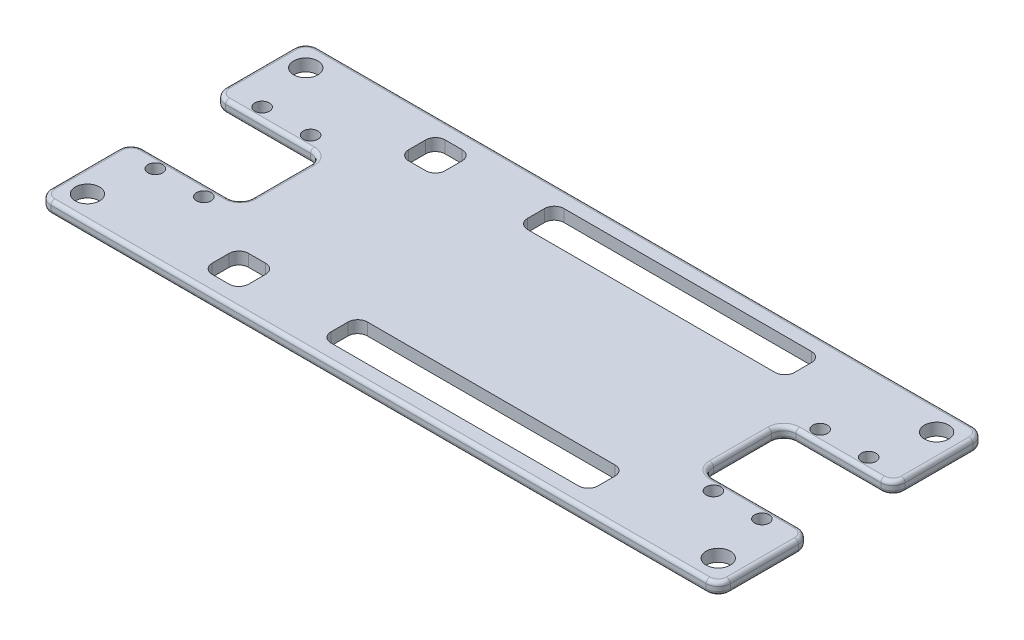
SolidWorks part; units mm, degrees
ref_plane "Front Plane" through (0, 0, 0) normal (0, 0, 1) x (1, 0, 0)
ref_plane "Top Plane" through (0, 0, 0) normal (0, 1, 0) x (1, 0, 0)
ref_plane "Right Plane" through (0, 0, 0) normal (1, 0, 0) x (0, 0, -1)
sketch "Sketch1" plane through (0, 0, 0) normal (0, 1, 0) x (1, 0, 0)
  line L1 (-88.9, -34.925) -> (88.9, -34.925)
  line L2 (-88.9, -34.925) -> (-88.9, 34.925)
  line L3 (-88.9, 34.925) -> (88.9, 34.925)
  line L4 (88.9, -34.925) -> (88.9, 34.925)
  line L5 (-88.9, -34.925) -> (88.9, 34.925) construction
  line L6 (-88.9, 34.925) -> (88.9, -34.925) construction
  point P0 (0, 0)
  dimension "D1" = 69.85
  dimension "D2" = 177.8
extrude "Boss-Extrude1" add sketch "Sketch1" along normal blind 3.175
sketch "Sketch2" plane through (0, 3.175, 0) normal (0, 1, 0) x (1, 0, 0)
  line L0 (-88.9, 34.925) -> (-88.9, -34.925) construction
  line L1 (-82.55, -28.575) -> (82.55, -28.575) construction
  line L2 (-82.55, -28.575) -> (-82.55, 28.575) construction
  line L3 (-82.55, 28.575) -> (82.55, 28.575) construction
  line L4 (82.55, -28.575) -> (82.55, 28.575) construction
  line L5 (-82.55, -28.575) -> (82.55, 28.575) construction
  line L6 (-82.55, 28.575) -> (82.55, -28.575) construction
  line L7 (88.9, 34.925) -> (-88.9, 34.925) construction
  line L9 (88.9, -34.925) -> (88.9, 34.925) construction
  line L10 (-60.325, -10.795) -> (-88.9, -10.795)
  line L11 (-60.325, -10.795) -> (-60.325, 10.795)
  line L12 (-60.325, 10.795) -> (-88.9, 10.795)
  line L13 (60.325, -10.795) -> (88.9, -10.795)
  line L14 (60.325, -10.795) -> (60.325, 10.795)
  line L15 (60.325, 10.795) -> (88.9, 10.795)
  line L16 (88.9, -10.795) -> (88.9, 10.795)
  line L17 (-88.9, 0) -> (96.9512, 0) construction
  line L18 (-88.9, -10.795) -> (-88.9, 10.795)
  line L19 (-60.325, -10.795) -> (-88.9, 10.795) construction
  line L20 (-60.325, 10.795) -> (-88.9, -10.795) construction
  line L21 (60.325, -10.795) -> (88.9, 10.795) construction
  line L22 (60.325, 10.795) -> (88.9, -10.795) construction
  line L23 (-88.9, 13.97) -> (88.9, 13.97) construction
  line L24 (-88.9, -13.97) -> (88.9, -13.97) construction
  circle A0 centre (-82.55, 28.575) radius 3.175
  circle A1 centre (-82.55, -28.575) radius 3.175
  circle A2 centre (82.55, 28.575) radius 3.175
  circle A3 centre (82.55, -28.575) radius 3.175
  circle A4 centre (-66.675, 13.97) radius 1.905
  circle A5 centre (-79.375, 13.97) radius 1.905
  circle A6 centre (-66.675, -13.97) radius 1.905
  circle A7 centre (-79.375, -13.97) radius 1.905
  circle A8 centre (66.675, 13.97) radius 1.905
  circle A9 centre (79.375, 13.97) radius 1.905
  circle A10 centre (66.675, -13.97) radius 1.905
  circle A11 centre (79.375, -13.97) radius 1.905
  point P0 (0, 0)
  point P14 (-74.6125, 0)
  point P18 (74.6125, 0)
  dimension "D1" = 6.35
  dimension "D2" = 6.35
  dimension "D3" = 6.35
  dimension "D4" = 6.35
  dimension "D12" = 3.81
  dimension "D5" = 6.35
  dimension "D6" = 6.35
  dimension "D7" = 28.575
  dimension "D8" = 21.59
  dimension "D9" = 3.175
  dimension "D10" = 3.175
  dimension "D11" = 12.7
  dimension "D13" = 9.525
  dimension "D14" = 12.7
  dimension "D15" = 9.525
extrude "Cut-Extrude1" cut sketch "Sketch2" against normal through all
fillet "Fillet1" radius 3.175 12 edges at (88.9, 1.5875, -34.925) (88.9, 1.5875, 34.925) (-88.9, 1.5875, -34.925) (-88.9, 1.5875, 34.925) (88.9, 1.5875, 10.795) (60.325, 1.5875, 10.795) (60.325, 1.5875, -10.795) (88.9, 1.5875, -10.795) (-88.9, 1.5875, 10.795) (-60.325, 1.5875, 10.795) (-60.325, 1.5875, -10.795) (-88.9, 1.5875, -10.795)
fillet "Fillet2" radius 1 48 edges at (-87.9701, 0, 33.9951) (-88.9, 0, 22.86) (-87.9701, 0, 11.7249) (-74.6125, 0, 10.795) (-61.2549, 0, 9.8651) (-60.325, 0, 0) (-61.2549, 0, -9.8651) (-74.6125, 0, -10.795) (-87.9701, 0, -11.7249) (-88.9, 0, -22.86) (-87.9701, 0, -33.9951) (0, 0, -34.925) (87.9701, 0, -33.9951) (88.9, 0, -22.86) (87.9701, 0, -11.7249) (74.6125, 0, -10.795) (61.2549, 0, -9.8651) (60.325, 0, 0) (61.2549, 0, 9.8651) (74.6125, 0, 10.795) (87.9701, 0, 11.7249) (88.9, 0, 22.86) (87.9701, 0, 33.9951) (-87.9701, 3.175, 33.9951) (-88.9, 3.175, 22.86) (-87.9701, 3.175, 11.7249) (-74.6125, 3.175, 10.795) (-61.2549, 3.175, 9.8651) (-60.325, 3.175, 0) (-61.2549, 3.175, -9.8651) (-74.6125, 3.175, -10.795) (-87.9701, 3.175, -11.7249) (-88.9, 3.175, -22.86) (-87.9701, 3.175, -33.9951) (0, 3.175, -34.925) (87.9701, 3.175, -33.9951) (88.9, 3.175, -22.86) (87.9701, 3.175, -11.7249) (74.6125, 3.175, -10.795) (61.2549, 3.175, -9.8651) (60.325, 3.175, 0) (61.2549, 3.175, 9.8651) (74.6125, 3.175, 10.795) (87.9701, 3.175, 11.7249) (88.9, 3.175, 22.86) (87.9701, 3.175, 33.9951) (0, 0, 34.925) (0, 3.175, 34.925)
sketch "Sketch3" plane through (0, 3.175, 0) normal (0, 1, 0) x (1, 0, 0)
  line L0 (50.435, 33.925) -> (50.435, -33.925) construction
  line L1 (85.725, 33.925) -> (-85.725, 33.925) construction
  line L2 (-85.725, -33.925) -> (85.725, -33.925) construction
  line L3 (-19.415, 33.925) -> (-19.415, -33.925) construction
  line L4 (-50.53, 33.925) -> (-50.53, -33.925) construction
  line L5 (-19.415, 30.48) -> (50.435, 30.48)
  line L6 (-19.415, 30.48) -> (-19.415, 20.955)
  line L7 (-19.415, 20.955) -> (50.435, 20.955)
  line L8 (50.435, 30.48) -> (50.435, 20.955)
  line L9 (50.435, -30.48) -> (-19.415, -30.48)
  line L10 (50.435, -30.48) -> (50.435, -20.955)
  line L11 (50.435, -20.955) -> (-19.415, -20.955)
  line L12 (-19.415, -30.48) -> (-19.415, -20.955)
  line L13 (59.325, -7.62) -> (59.325, 7.62) construction
  line L14 (-50.53, 30.48) -> (-41.005, 30.48)
  line L15 (-50.53, 30.48) -> (-50.53, 20.955)
  line L16 (-50.53, 20.955) -> (-41.005, 20.955)
  line L17 (-41.005, 30.48) -> (-41.005, 20.955)
  line L18 (-50.53, -20.955) -> (-41.005, -20.955)
  line L19 (-50.53, -20.955) -> (-50.53, -30.48)
  line L20 (-50.53, -30.48) -> (-41.005, -30.48)
  line L21 (-41.005, -20.955) -> (-41.005, -30.48)
  line L22 (0, 33.925) -> (0, -33.925) construction
  line L23 (15.51, 20.955) -> (15.51, -20.955) construction
  line L24 (15.51, 0) -> (0, 0) construction
  dimension "D1" = 69.85
  dimension "D2" = 21.59
  dimension "D3" = 9.525
  dimension "D4" = 9.525
  dimension "D5" = 9.525
  dimension "D6" = 8.89
  dimension "D7" = 41.91
extrude "Cut-Extrude2" cut sketch "Sketch3" against normal through all
fillet "Fillet3" radius 2.54 16 edges at (-50.53, 1.5875, 20.955) (-50.53, 1.5875, 30.48) (-41.005, 1.5875, 30.48) (-41.005, 1.5875, 20.955) (-19.415, 1.5875, 30.48) (-19.415, 1.5875, 20.955) (50.435, 1.5875, 20.955) (50.435, 1.5875, 30.48) (50.435, 1.5875, -20.955) (50.435, 1.5875, -30.48) (-19.415, 1.5875, -20.955) (-19.415, 1.5875, -30.48) (-50.53, 1.5875, -20.955) (-41.005, 1.5875, -20.955) (-41.005, 1.5875, -30.48) (-50.53, 1.5875, -30.48)
